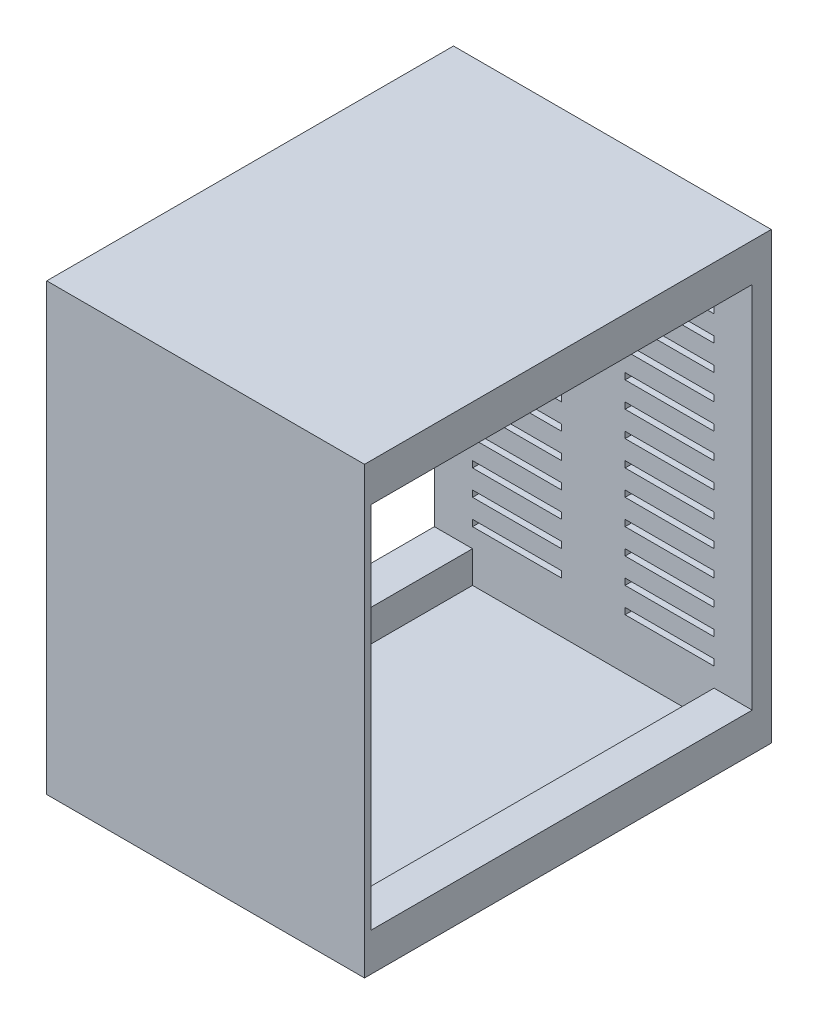
SolidWorks part; units mm, degrees
ref_plane "Alzado" through (0, 0, 0) normal (0, 0, 1) x (1, 0, 0)
ref_plane "Planta" through (0, 0, 0) normal (0, 1, 0) x (1, 0, 0)
ref_plane "Vista lateral" through (0, 0, 0) normal (1, 0, 0) x (0, 0, -1)
sketch "Croquis1" plane through (0, 0, 0) normal (0, 0, 1) x (1, 0, 0)
  line L1 (-125, -175) -> (125, -175)
  line L2 (-125, -175) -> (-125, 175)
  line L3 (-125, 175) -> (125, 175)
  line L4 (125, -175) -> (125, 175)
  line L5 (-125, -175) -> (125, 175) construction
  line L6 (-125, 175) -> (125, -175) construction
  point P0 (0, 0)
  dimension "D1" = 250
  dimension "D2" = 350
extrude "Saliente-Extruir2" add sketch "Croquis1" along normal blind 15 contours L3 L4 L1 L2
sketch "Croquis2" plane through (0, 0, 15) normal (0, 0, 1) x (1, 0, 0)
  line L1 (-125, 175) -> (-95, 175)
  line L2 (-125, 175) -> (-125, 145)
  line L3 (-125, 145) -> (-95, 145)
  line L4 (-95, 175) -> (-95, 145)
  line L5 (125, 175) -> (95, 175)
  line L6 (125, 175) -> (125, 145)
  line L7 (125, 145) -> (95, 145)
  line L8 (95, 175) -> (95, 145)
  line L9 (-125, -175) -> (-95, -175)
  line L10 (-125, -175) -> (-125, -145)
  line L11 (-125, -145) -> (-95, -145)
  line L12 (-95, -175) -> (-95, -145)
  line L13 (125, -175) -> (95, -175)
  line L14 (125, -175) -> (125, -145)
  line L15 (125, -145) -> (95, -145)
  line L16 (95, -175) -> (95, -145)
  dimension "D1" = 30
  dimension "D2" = 30
extrude "Saliente-Extruir3" add sketch "Croquis2" along normal blind 300
sketch "Croquis3" plane through (0, 0, 315) normal (0, 0, 1) x (1, 0, 0)
  line L1 (-125, 175) -> (125, 175)
  line L2 (-125, 175) -> (-125, -175)
  line L3 (-125, -175) -> (125, -175)
  line L4 (125, 175) -> (125, -175)
extrude "Saliente-Extruir4" add sketch "Croquis3" along normal blind 5
sketch "Croquis7" plane through (0, 0, 0) normal (0, 0, -1) x (-1, 0, 0)
  line L0 (25, 135) -> (95, 135)
  line L1 (-95, 135) -> (-25, 135)
  line L2 (-95, 135) -> (-95, 130)
  line L3 (-95, 130) -> (-25, 130)
  line L4 (-25, 135) -> (-25, 130)
  line L5 (95, 135) -> (95, 130)
  line L6 (25, 130) -> (95, 130)
  line L7 (25, 135) -> (25, 130)
  line L8 (25, 115) -> (95, 115)
  line L9 (95, 115) -> (95, 110)
  line L10 (25, 110) -> (95, 110)
  line L11 (25, 115) -> (25, 110)
  line L12 (25, 95) -> (95, 95)
  line L13 (95, 95) -> (95, 90)
  line L14 (25, 90) -> (95, 90)
  line L15 (25, 95) -> (25, 90)
  line L16 (25, 75) -> (95, 75)
  line L17 (95, 75) -> (95, 70)
  line L18 (25, 70) -> (95, 70)
  line L19 (25, 75) -> (25, 70)
  line L20 (25, 55) -> (95, 55)
  line L21 (95, 55) -> (95, 50)
  line L22 (25, 50) -> (95, 50)
  line L23 (25, 55) -> (25, 50)
  line L24 (25, 35) -> (95, 35)
  line L25 (95, 35) -> (95, 30)
  line L26 (25, 30) -> (95, 30)
  line L27 (25, 35) -> (25, 30)
  line L28 (25, 15) -> (95, 15)
  line L29 (95, 15) -> (95, 10)
  line L30 (25, 10) -> (95, 10)
  line L31 (25, 15) -> (25, 10)
  line L32 (25, -5) -> (95, -5)
  line L33 (95, -5) -> (95, -10)
  line L34 (25, -10) -> (95, -10)
  line L35 (25, -5) -> (25, -10)
  line L36 (25, -25) -> (95, -25)
  line L37 (95, -25) -> (95, -30)
  line L38 (25, -30) -> (95, -30)
  line L39 (25, -25) -> (25, -30)
  line L40 (25, -45) -> (95, -45)
  line L41 (95, -45) -> (95, -50)
  line L42 (25, -50) -> (95, -50)
  line L43 (25, -45) -> (25, -50)
  line L64 (-95, 115) -> (-25, 115)
  line L65 (-25, 115) -> (-25, 110)
  line L66 (-95, 110) -> (-25, 110)
  line L67 (-95, 115) -> (-95, 110)
  line L68 (-95, 95) -> (-25, 95)
  line L69 (-25, 95) -> (-25, 90)
  line L70 (-95, 90) -> (-25, 90)
  line L71 (-95, 95) -> (-95, 90)
  line L72 (-95, 75) -> (-25, 75)
  line L73 (-25, 75) -> (-25, 70)
  line L74 (-95, 70) -> (-25, 70)
  line L75 (-95, 75) -> (-95, 70)
  line L76 (-95, 55) -> (-25, 55)
  line L77 (-25, 55) -> (-25, 50)
  line L78 (-95, 50) -> (-25, 50)
  line L79 (-95, 55) -> (-95, 50)
  line L80 (-95, 35) -> (-25, 35)
  line L81 (-25, 35) -> (-25, 30)
  line L82 (-95, 30) -> (-25, 30)
  line L83 (-95, 35) -> (-95, 30)
  line L84 (-95, 15) -> (-25, 15)
  line L85 (-25, 15) -> (-25, 10)
  line L86 (-95, 10) -> (-25, 10)
  line L87 (-95, 15) -> (-95, 10)
  line L88 (-95, -5) -> (-25, -5)
  line L89 (-25, -5) -> (-25, -10)
  line L90 (-95, -10) -> (-25, -10)
  line L91 (-95, -5) -> (-95, -10)
  line L92 (-95, -25) -> (-25, -25)
  line L93 (-25, -25) -> (-25, -30)
  line L94 (-95, -30) -> (-25, -30)
  line L95 (-95, -25) -> (-95, -30)
  line L96 (-95, -45) -> (-25, -45)
  line L97 (-25, -45) -> (-25, -50)
  line L98 (-95, -50) -> (-25, -50)
  line L99 (-95, -45) -> (-95, -50)
  line L120 (-95, -65) -> (-25, -65)
  line L121 (-25, -65) -> (-25, -70)
  line L122 (-95, -70) -> (-25, -70)
  line L123 (-95, -65) -> (-95, -70)
  line L124 (25, -65) -> (95, -65)
  line L125 (95, -65) -> (95, -70)
  line L126 (25, -70) -> (95, -70)
  line L127 (25, -65) -> (25, -70)
  line L128 (-95, -85) -> (-25, -85)
  line L129 (-25, -85) -> (-25, -90)
  line L130 (-95, -90) -> (-25, -90)
  line L131 (-95, -85) -> (-95, -90)
  line L132 (25, -85) -> (95, -85)
  line L133 (95, -85) -> (95, -90)
  line L134 (25, -90) -> (95, -90)
  line L135 (25, -85) -> (25, -90)
  line L136 (-95, -105) -> (-25, -105)
  line L137 (-25, -105) -> (-25, -110)
  line L138 (-95, -110) -> (-25, -110)
  line L139 (-95, -105) -> (-95, -110)
  line L140 (25, -105) -> (95, -105)
  line L141 (95, -105) -> (95, -110)
  line L142 (25, -110) -> (95, -110)
  line L143 (25, -105) -> (25, -110)
  line L144 (-95, -125) -> (-25, -125)
  line L145 (-25, -125) -> (-25, -130)
  line L146 (-95, -130) -> (-25, -130)
  line L147 (-95, -125) -> (-95, -130)
  line L148 (25, -125) -> (95, -125)
  line L149 (95, -125) -> (95, -130)
  line L150 (25, -130) -> (95, -130)
  line L151 (25, -125) -> (25, -130)
  line L152 (-95, 135) -> (-95, 175) construction
  line L153 (125, 175) -> (-125, 175) construction
  line L154 (-95, 135) -> (-125, 135) construction
  line L155 (-125, -175) -> (-125, 175) construction
  line L156 (-95, 130) -> (-125, 130) construction
  line L157 (95, 135) -> (125, 135) construction
  line L158 (125, -175) -> (125, 175) construction
  dimension "D1" = 5
  dimension "D2" = 70
  dimension "D5" = 40
  dimension "D3" = 2
  dimension "D4" = 14
extrude "Cortar-Extruir1" cut sketch "Croquis7" against normal blind 20
sketch "Croquis8" plane through (0, -175, 0) normal (0, -1, 0) x (1, 0, 0)
  line L1 (-125, 320) -> (125, 320)
  line L2 (-125, 320) -> (-125, 0)
  line L3 (-125, 0) -> (125, 0)
  line L4 (125, 320) -> (125, 0)
extrude "Saliente-Extruir5" add sketch "Croquis8" against normal blind 5
sketch "Croquis9" plane through (0, 175, 0) normal (0, 1, 0) x (1, 0, 0)
  line L1 (125, -320) -> (-125, -320)
  line L2 (125, -320) -> (125, 0)
  line L3 (125, 0) -> (-125, 0)
  line L4 (-125, -320) -> (-125, 0)
extrude "Saliente-Extruir6" add sketch "Croquis9" against normal blind 5
